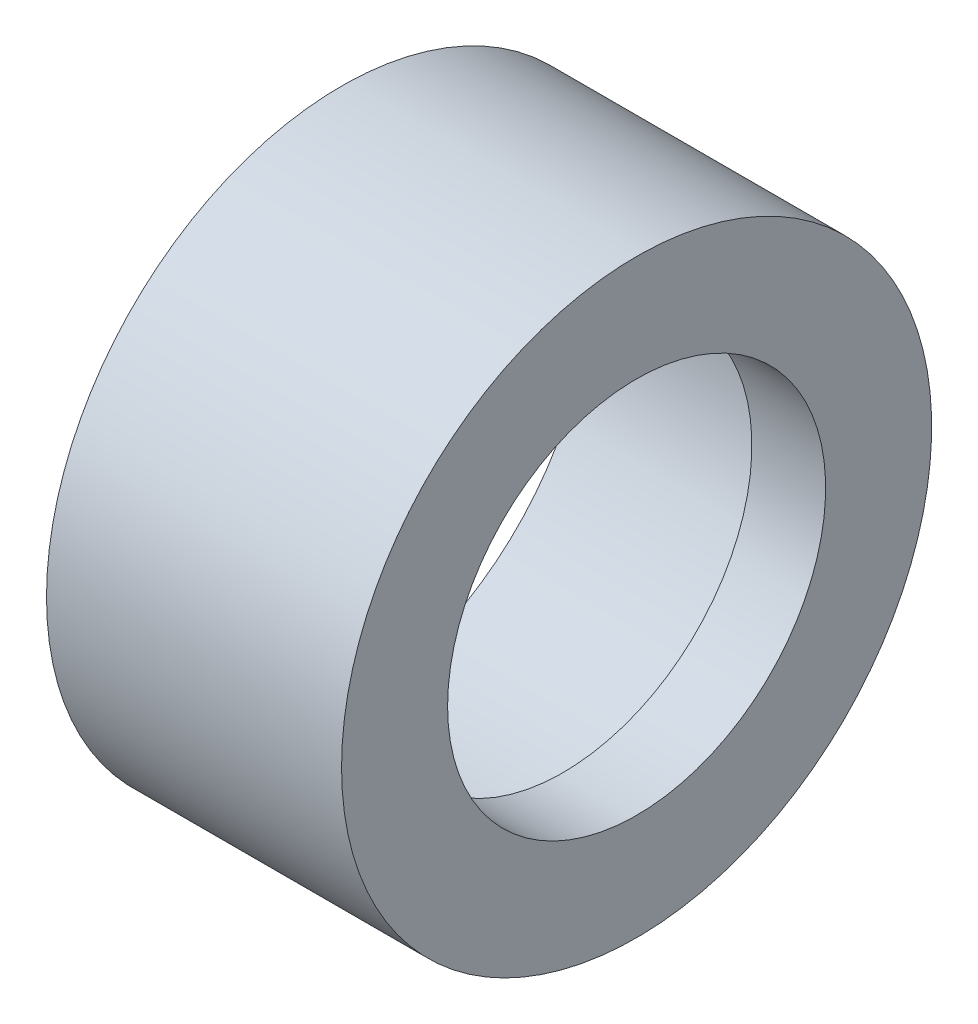
SolidWorks part; units mm, degrees
material "AISI 304"
ref_plane "前视基准面" through (0, 0, 0) normal (0, 0, 1) x (1, 0, 0)
ref_plane "上视基准面" through (0, 0, 0) normal (0, 1, 0) x (1, 0, 0)
ref_plane "右视基准面" through (0, 0, 0) normal (1, 0, 0) x (0, 0, -1)
sketch "草图1" plane through (0, 0, 0) normal (0, 0, 1) x (1, 0, 0)
  line L0 (0, 0) -> (8.6722, 0) construction
  line L1 (0, 3.3625) -> (3, 3.3625)
  line L2 (3, 3.3625) -> (3, 2.5625)
  line L3 (3, 2.5625) -> (4, 2.5625)
  line L4 (4, 2.5625) -> (4, 4)
  line L5 (4, 4) -> (0, 4)
  line L6 (0, 4) -> (0, 3.3625)
  dimension "D1" = 3.3625
  dimension "D2" = 4
  dimension "D3" = 1
  dimension "D4" = 0.8
  dimension "D5" = 3
revolve "旋转1" add sketch "草图1" angle 360 about L0
